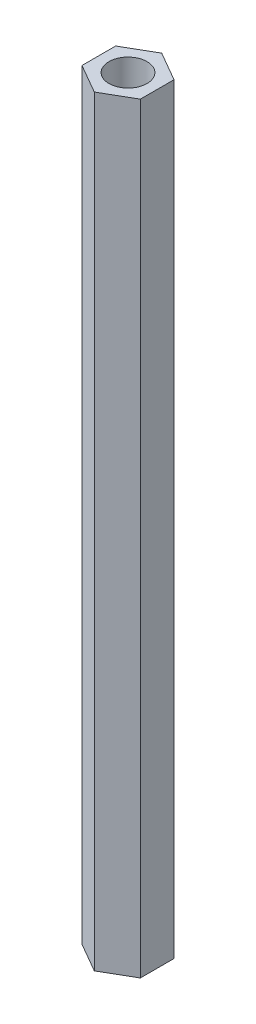
SolidWorks part; units mm, degrees
material "黄铜"
ref_plane "前视基准面" through (0, 0, 0) normal (0, 0, 1) x (1, 0, 0)
ref_plane "上视基准面" through (0, 0, 0) normal (0, 1, 0) x (1, 0, 0)
ref_plane "右视基准面" through (0, 0, 0) normal (1, 0, 0) x (0, 0, -1)
sketch "草图1" plane through (0, 0, 0) normal (0, 1, 0) x (1, 0, 0)
  line L1 (0, 2.6558) -> (-2.3, 1.3279)
  line L2 (-2.3, 1.3279) -> (-2.3, -1.3279)
  line L3 (-2.3, -1.3279) -> (0, -2.6558)
  line L4 (0, -2.6558) -> (2.3, -1.3279)
  line L5 (2.3, -1.3279) -> (2.3, 1.3279)
  line L6 (2.3, 1.3279) -> (0, 2.6558)
  circle A0 centre (0, 0) radius 2.3 construction
  circle A1 centre (0, 0) radius 1.5
  dimension "D2" = 3
  dimension "D1" = 4.6
extrude "凸台-拉伸1" add sketch "草图1" along normal blind 60
